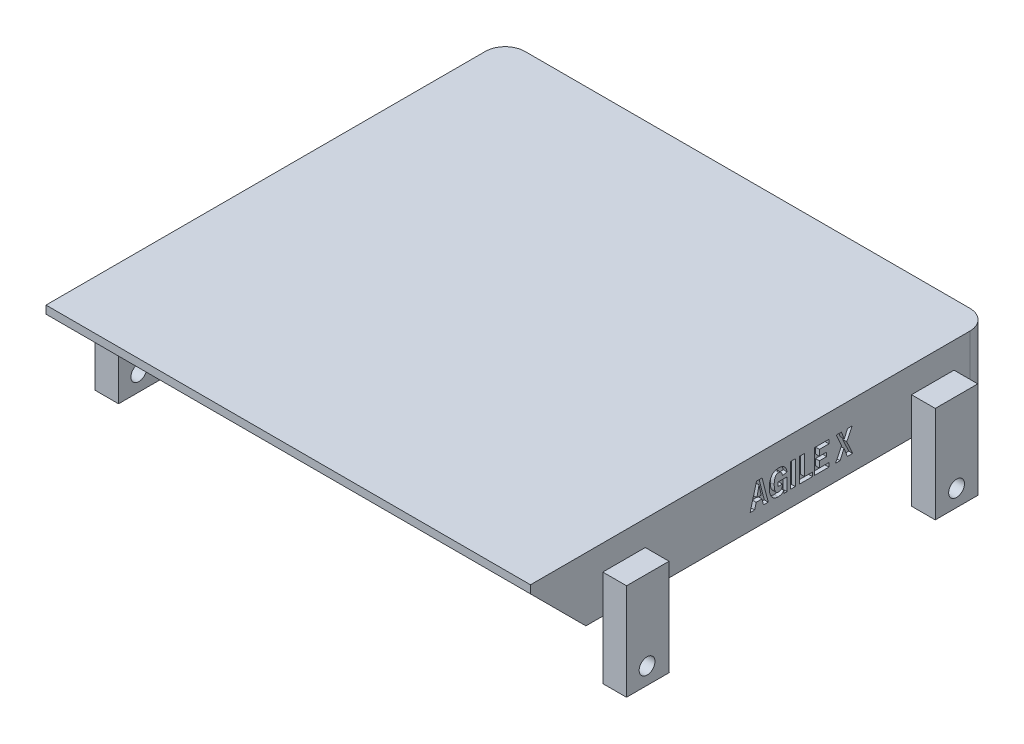
SolidWorks part; units mm, degrees
ref_plane "Front Plane" through (0, 0, 0) normal (0, 0, 1) x (1, 0, 0)
ref_plane "Top Plane" through (0, 0, 0) normal (0, 1, 0) x (1, 0, 0)
ref_plane "Right Plane" through (0, 0, 0) normal (1, 0, 0) x (0, 0, -1)
sketch "Sketch1" plane through (0, 0, 0) normal (0, 1, 0) x (1, 0, 0)
  line L1 (306, -206.9692) -> (-306, -206.9692)
  line L2 (306, -206.9692) -> (306, 373.0308)
  line L3 (306, 373.0308) -> (-306, 373.0308)
  line L4 (-306, -206.9692) -> (-306, 373.0308)
  line L5 (306, -206.9692) -> (-306, 373.0308) construction
  line L6 (306, 373.0308) -> (-306, -206.9692) construction
  point P0 (0, 0)
  dimension "D1" = 612
  dimension "D3" = 580
extrude "Boss-Extrude1" add sketch "Sketch1" along normal blind 80
chamfer "Chamfer1" distance 70 angle 45 1 edges at (0, 0, 206.9692)
fillet "Fillet2" radius 25 2 edges at (306, 40, -373.0308) (-306, 40, -373.0308)
sketch "Sketch2" plane through (0, -68.4846, 68.4846) normal (0, -0.7071, 0.7071) x (1, 0, 0)
  line L0 (-306, 146.3493) -> (306, 146.3493) construction
  text T0 "<b>SCOUT MN</b>\r\n\r\n" font "Franklin Gothic Medium Cond" height 30
extrude "Cut-Extrude1" cut sketch "Sketch2" against normal blind 5
sketch "Sketch3" plane through (306, 0, 0) normal (1, 0, 0) x (0, 0, -1)
  line L0 (-171.9692, 35) -> (348.0308, 40) construction
  text T0 "<b>AGILE X</b>" font "Franklin Gothic Medium Cond" height 30
extrude "Cut-Extrude2" cut sketch "Sketch3" against normal blind 5
sketch "Sketch4" plane through (306, 0, 0) normal (1, 0, 0) x (0, 0, -1)
  line L0 (274.325, 47.2735) -> (328.0412, 47.2735)
  line L1 (-115.6222, 48.2367) -> (-61.967, 48.2367)
  line L2 (-115.6222, 48.2367) -> (-115.6832, -73.7633)
  line L3 (-115.6832, -73.7633) -> (-61.6832, -73.7633)
  line L4 (-61.967, 48.2367) -> (-61.6832, -73.7633)
  line L7 (274.325, 47.2735) -> (274.325, -74.7265)
  line L8 (274.325, -74.7265) -> (328.325, -74.7265)
  line L9 (328.0412, 47.2735) -> (328.325, -74.7265)
  line L10 (-115.6222, 48.2367) -> (328.0412, 47.2735) construction
  line L11 (301.2138, 46.4723) -> (301.3555, -74.7265) construction
  line L12 (-88.7946, 47.5996) -> (-88.6527, -73.7633) construction
  circle A0 centre (-89.7025, -52.4004) radius 10
  circle A1 centre (301.2481, -53.5277) radius 10
  point P0 (-110.8929, 39.894)
  point P17 (0, 0)
  point P18 (0, 0)
  dimension "D1" = 100
  dimension "D7" = 20
  dimension "D8" = 20
  dimension "D2" = 100
  dimension "D3" = 122
  dimension "D4" = 122
  dimension "D5" = 54
  dimension "D6" = 54
extrude "Boss-Extrude2" add sketch "Sketch4" along normal blind 30
sketch "Sketch6" plane through (-306, 0, 0) normal (-1, 0, 0) x (0, 0, 1)
  line L0 (-274.473, 47.2821) -> (-328.473, 47.2821)
  line L1 (115.3244, 48.133) -> (61.3244, 48.133)
  line L2 (115.3244, 48.133) -> (115.3244, -73.867)
  line L3 (115.3244, -73.867) -> (61.3244, -73.867)
  line L4 (61.3244, 48.133) -> (61.3244, -73.867)
  line L5 (115.3244, 48.133) -> (61.3244, -73.867) construction
  line L6 (115.3244, -73.867) -> (61.3244, 48.133) construction
  line L7 (-274.473, 47.2821) -> (-274.473, -74.7179)
  line L8 (-274.473, -74.7179) -> (-328.473, -74.7179)
  line L9 (-328.473, 47.2821) -> (-328.473, -74.7179)
  circle A0 centre (89.7025, -52.4004) radius 10
  circle A1 centre (-301.0474, -53.9064) radius 10
  point P0 (89.0604, 49.1913)
  dimension "D3" = 20
  dimension "D4" = 20
  dimension "D1" = 54
  dimension "D2" = 122
extrude "Boss-Extrude3" add sketch "Sketch6" along normal blind 30
